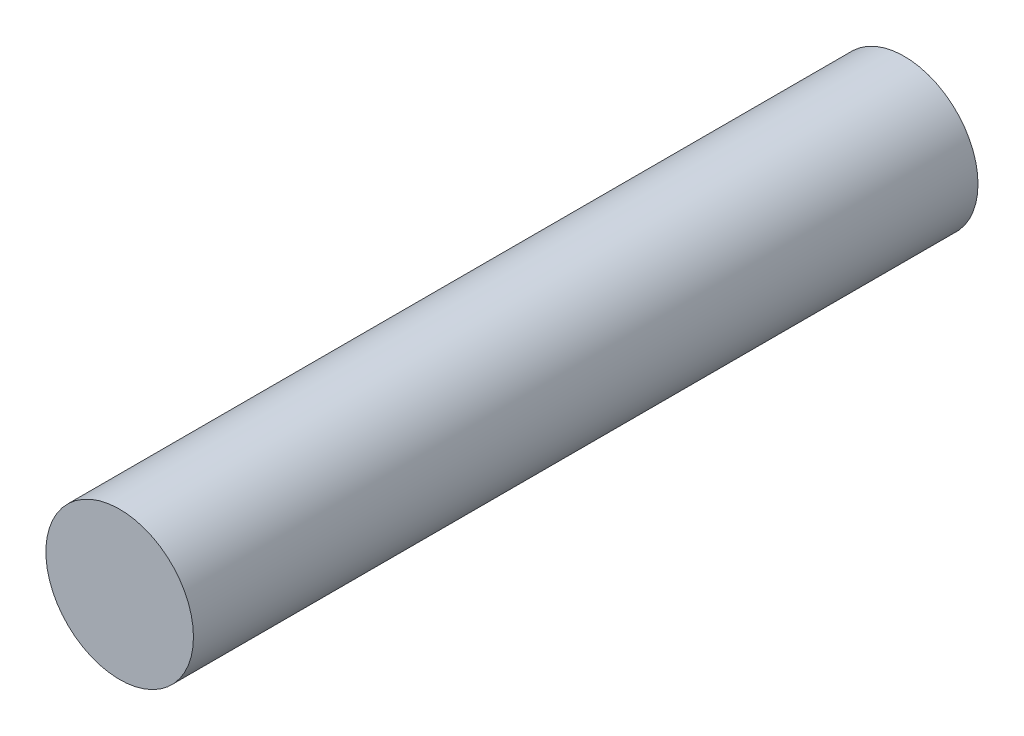
SolidWorks part; units mm, degrees
ref_plane "Front Plane" through (0, 0, 0) normal (0, 0, 1) x (1, 0, 0)
ref_plane "Top Plane" through (0, 0, 0) normal (0, 1, 0) x (1, 0, 0)
ref_plane "Right Plane" through (0, 0, 0) normal (1, 0, 0) x (0, 0, -1)
sketch "Sketch1" plane through (0, 0, 0) normal (0, 0, 1) x (1, 0, 0)
  circle A0 centre (0, 0) radius 1.505
  dimension "D1" = 3.01
extrude "Boss-Extrude1" add sketch "Sketch1" along normal blind 16
